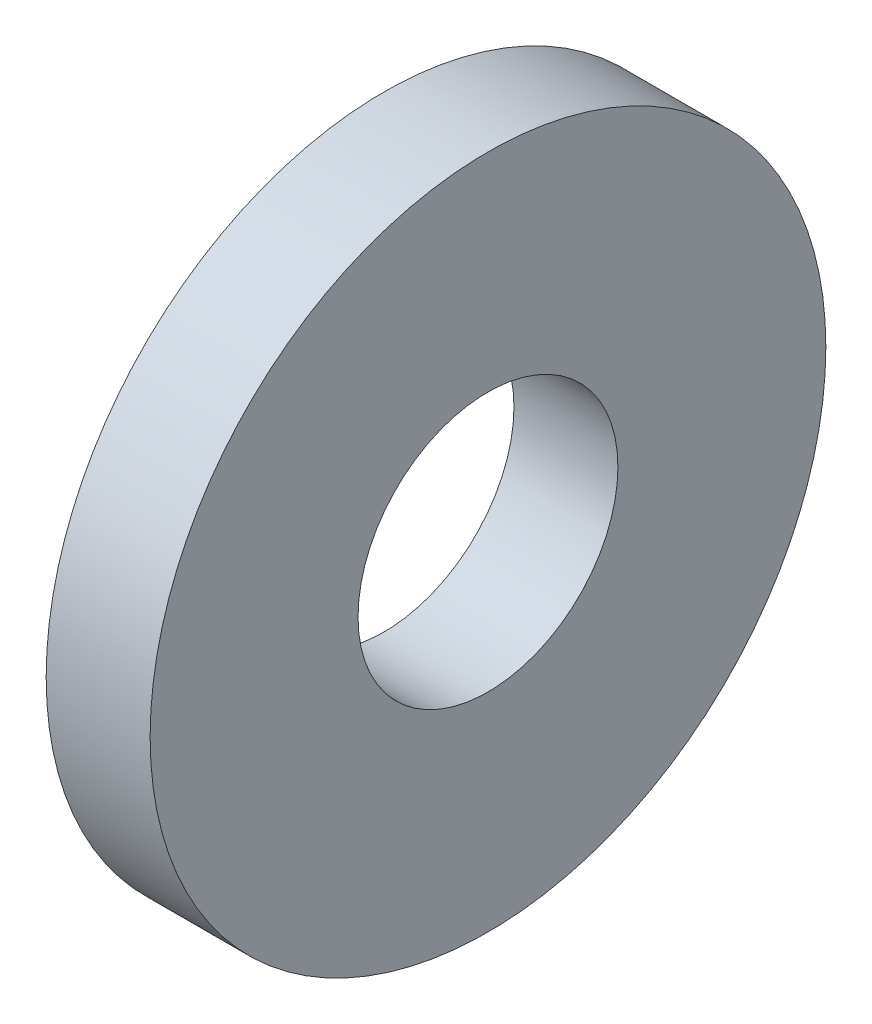
SolidWorks part; units mm, degrees
material "AISI 304"
ref_plane "Front Plane" through (0, 0, 0) normal (0, 0, 1) x (1, 0, 0)
ref_plane "Top Plane" through (0, 0, 0) normal (0, 1, 0) x (1, 0, 0)
ref_plane "Right Plane" through (0, 0, 0) normal (1, 0, 0) x (0, 0, -1)
ref_plane "Plane1" through (0, 0, 0) normal (0, 0, -1) x (-1, 0, 0)
sketch "Sketch1" plane through (0, 0, 0) normal (0, 0, -1) x (-1, 0, 0)
  line L0 (1, 6.5) -> (-1, 6.5)
  line L1 (-1, 6.5) -> (-1, 2.5)
  line L2 (-1, 2.5) -> (1, 2.5)
  line L3 (1, 2.5) -> (1, 6.5)
  line L4 (-1, 0) -> (1, 0) construction
revolve "Revolve1" add sketch "Sketch1" angle 360 about L4
